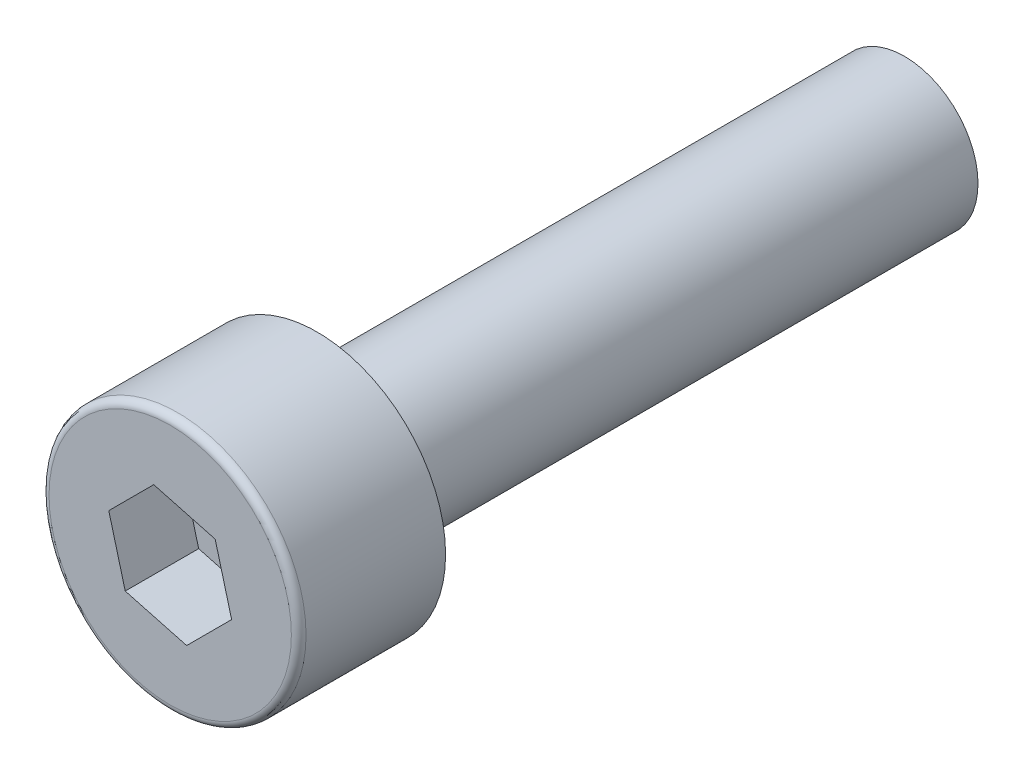
SolidWorks part; units mm, degrees
ref_plane "前视基准面" through (0, 0, 0) normal (0, 0, 1) x (1, 0, 0)
ref_plane "上视基准面" through (0, 0, 0) normal (0, 1, 0) x (1, 0, 0)
ref_plane "右视基准面" through (0, 0, 0) normal (1, 0, 0) x (0, 0, -1)
sketch "草图1" plane through (0, 0, 0) normal (0, 0, 1) x (1, 0, 0)
  circle A0 centre (0, 0) radius 3.5
  dimension "D1" = 7
extrude "凸台-拉伸1" add sketch "草图1" along normal blind 4
sketch "草图2" plane through (0, 0, 4) normal (0, 0, 1) x (1, 0, 0)
  line L1 (-1.2247, -1.2247) -> (0.4483, -1.673)
  line L2 (0.4483, -1.673) -> (1.673, -0.4483)
  line L3 (1.673, -0.4483) -> (1.2247, 1.2247)
  line L4 (1.2247, 1.2247) -> (-0.4483, 1.673)
  line L5 (-0.4483, 1.673) -> (-1.673, 0.4483)
  line L6 (-1.673, 0.4483) -> (-1.2247, -1.2247)
  circle A0 centre (0, 0) radius 1.5 construction
  dimension "D1" = 3
extrude "切除-拉伸1" cut sketch "草图2" against normal blind 2
sketch "草图3" plane through (0, 0, 0) normal (0, 0, -1) x (-1, 0, 0)
  circle A0 centre (0, 0) radius 2
  dimension "D1" = 4
extrude "凸台-拉伸2" add sketch "草图3" along normal blind 16
fillet "圆角1" radius 0.2 1 edges at (3.5, 0, 4)
